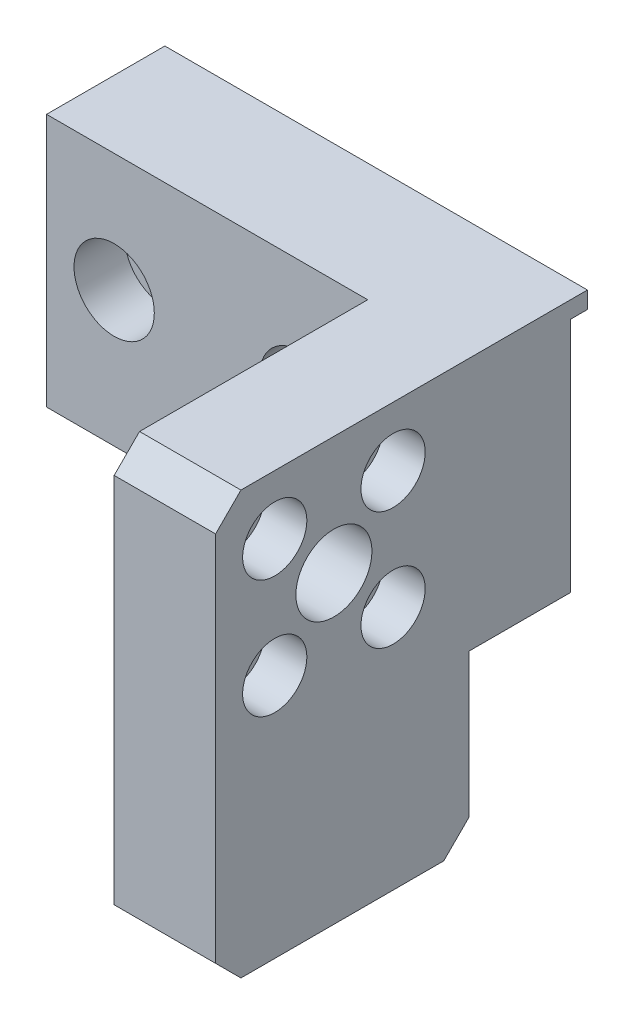
SolidWorks part; units mm, degrees
ref_plane "前视基准面" through (0, 0, 0) normal (0, 0, 1) x (1, 0, 0)
ref_plane "上视基准面" through (0, 0, 0) normal (0, 1, 0) x (1, 0, 0)
ref_plane "右视基准面" through (0, 0, 0) normal (1, 0, 0) x (0, 0, -1)
sketch "草图1" plane through (0, 0, 0) normal (0, 1, 0) x (1, 0, 0)
  line L0 (-25, 0) -> (25, 0)
  line L3 (25, 0) -> (25, -44)
  line L4 (25, -44) -> (13, -44)
  line L5 (13, -44) -> (13, -14)
  line L6 (13, -14) -> (-25, -14)
  line L7 (-25, -14) -> (-25, 0)
  line L8 (0, 0) -> (0, -87.9267) construction
  dimension "D1" = 50
  dimension "D2" = 14
  dimension "D3" = 12
  dimension "D4" = 44
extrude "凸台-拉伸1" add sketch "草图1" along normal mid plane 30
sketch "草图2" plane through (13, 0, 0) normal (1, 0, 0) x (0, 0, -1)
  line L0 (-44, 15) -> (0, 15) construction
  line L1 (-44, 15) -> (-44, -15) construction
  circle A0 centre (-30, 1) radius 6
  dimension "D3" = 12
  dimension "D1" = 14
  dimension "D2" = 14
extrude "切除-拉伸1" cut sketch "草图2" along normal blind 4
sketch "草图3" plane through (25, 0, 0) normal (1, 0, 0) x (0, 0, -1)
  circle A0 centre (-30, 1) radius 4.5
  dimension "D1" = 9
extrude "切除-拉伸2" cut sketch "草图3" against normal through all
hole_wizard "孔1" positions "草图5" profile "草图4" legacy
sketch "草图5" plane through (25, 11.7549, 2.8304) normal (1, 0, 0) x (0, 0, -1)
  line L0 (-27.1696, -10.7549) -> (-27.1696, 19.243) construction
  line L2 (-27.1696, -10.7549) -> (-56.8126, -10.7549) construction
  point P0 (-20.1696, -3.7549)
  point P1 (-34.1696, -3.7549)
  point P14 (-20.1696, -17.7549)
  point P15 (-34.1696, -17.7549)
  dimension "D1" = 14
  dimension "D2" = 14
sketch "草图4" plane through (25, 8, 23) normal (0, 1, 0) x (0, 0, -1)
  line L0 (0, 0) -> (0, 100)
  line L1 (0, 100) -> (2.25, 100)
  line L2 (2.25, 100) -> (2.25, 5)
  line L3 (2.25, 5) -> (3.8, 5)
  line L4 (3.8, 5) -> (3.8, 0)
  line L5 (3.8, 0) -> (0, 0)
  line L6 (0, 110) -> (0, -10) construction
  dimension "直径" = 4.5
  dimension "深度" = 100
  dimension "柱坑直径" = 7.6
  dimension "柱坑深度" = 5
hole_wizard "孔2" positions "草图7" profile "草图6" legacy
sketch "草图7" plane through (-5.0533, -5.2946, 14) normal (0, 0, 1) x (1, 0, 0)
  line L3 (-0.9467, 20.2946) -> (-0.9467, -9.2908) construction
  line L4 (-19.9467, 20.2946) -> (18.0533, 20.2946) construction
  point P0 (10.0533, 6.2946)
  point P1 (-11.9467, 6.2946)
  dimension "D1" = 22
  dimension "D2" = 14
sketch "草图6" plane through (5, 1, 14) normal (1, 0, 0) x (0, -1, 0)
  line L0 (0, 0) -> (0, 100)
  line L1 (0, 100) -> (2.75, 100)
  line L2 (2.75, 100) -> (2.75, 6)
  line L3 (2.75, 6) -> (4.75, 6)
  line L4 (4.75, 6) -> (4.75, 0)
  line L5 (4.75, 0) -> (0, 0)
  line L6 (0, 110) -> (0, -10) construction
  dimension "直径" = 5.5
  dimension "深度" = 100
  dimension "柱坑直径" = 9.5
  dimension "柱坑深度" = 6
sketch "草图8" plane through (0, -15, 0) normal (0, -1, 0) x (1, 0, 0)
  line L0 (25, 44) -> (25, 0) construction
  line L1 (13, 44) -> (25, 44)
  line L2 (13, 44) -> (13, 14)
  line L3 (13, 14) -> (25, 14)
  line L4 (25, 44) -> (25, 14)
  line L5 (-25, 14) -> (13, 14) construction
extrude "凸台-拉伸2" add sketch "草图8" along normal blind 20
chamfer "倒角1" distance 3 angle 45 3 edges at (19, 15, 44) (19, -35, 44) (19, -35, 14)
sketch "草图10" plane through (25, 0, 0) normal (1, 0, 0) x (0, 0, -1)
  line L1 (0, -15) -> (-2, -15)
  line L2 (0, -15) -> (0, 13)
  line L3 (0, 13) -> (-2, 13)
  line L4 (-2, -15) -> (-2, 13)
  line L5 (-41, 15) -> (0, 15) construction
  dimension "D1" = 2
  dimension "D2" = 2
extrude "切除-拉伸4" cut sketch "草图10" against normal through all
